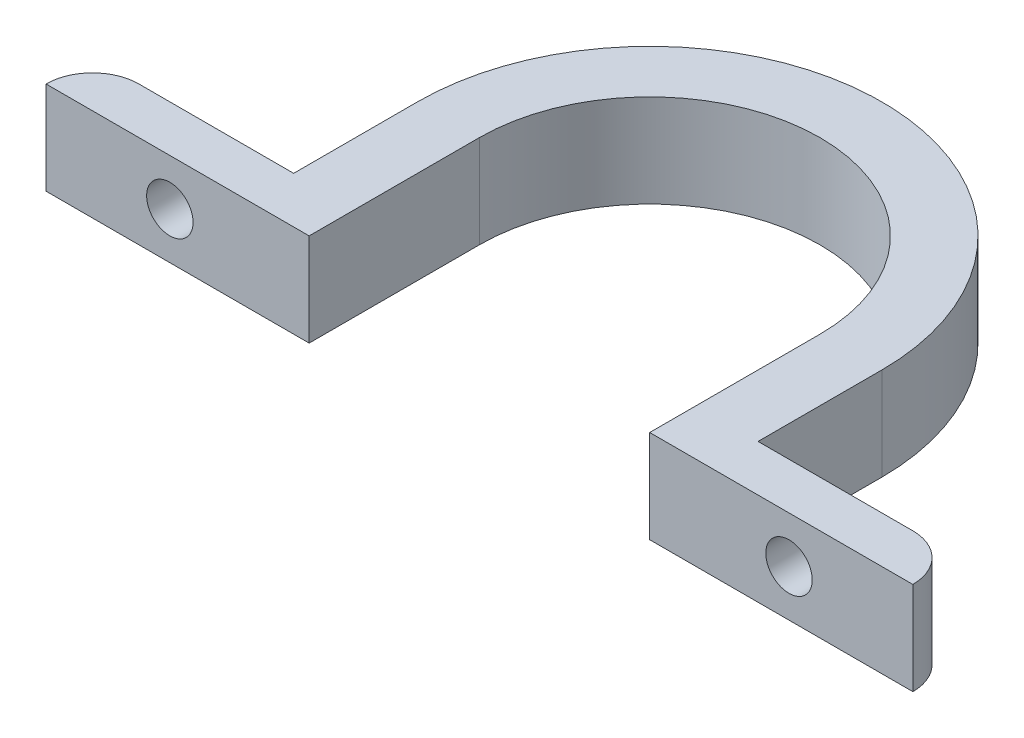
SolidWorks part; units mm, degrees
ref_plane "Plan de face" through (0, 0, 0) normal (0, 0, 1) x (1, 0, 0)
ref_plane "Plan de dessus" through (0, 0, 0) normal (0, 1, 0) x (1, 0, 0)
ref_plane "Plan de droite" through (0, 0, 0) normal (1, 0, 0) x (0, 0, -1)
sketch "Esquisse1" plane through (0, 0, 0) normal (0, 1, 0) x (1, 0, 0)
  line L2 (24, 0.5) -> (24, -10.5)
  line L3 (24, -10.5) -> (41, -10.5)
  line L4 (38, -7.5) -> (28, -7.5)
  line L6 (13, 0) -> (13, 17.6683) construction
  line L7 (13, -10.5) -> (-3.8365, -10.5) construction
  line L8 (38, -6.3228) -> (38, 14.4487) construction
  line L14 (28, -7.5) -> (28, 0.5)
  line L15 (2, -10.5) -> (-15, -10.5)
  line L16 (2, 0.5) -> (2, -10.5)
  line L17 (-2, -7.5) -> (-2, 0.5)
  line L18 (-12, -7.5) -> (-2, -7.5)
  arc A0 (2, 0.5) -> (24, 0.5) centre (13, 0.5) cw
  arc A1 (-2, 0.5) -> (28, 0.5) centre (13, 0.5) cw
  circle A2 centre (13, 0.5) radius 11 construction
  arc A3 (41, -10.5) -> (38, -7.5) centre (38, -10.5) ccw
  arc A4 (-15, -10.5) -> (-12, -7.5) centre (-12, -10.5) cw
  dimension "D1" = 11
  dimension "D2" = 15
  dimension "D3" = 3
  dimension "D6" = 10
  dimension "D4" = 4
  dimension "D5" = 3
extrude "Boss.-Extru.2" add sketch "Esquisse1" along normal blind 6
ref_plane "Plan1" through (-12, 6, 7.5) normal (-1, 0, 0) x (0, 0, 1)
sketch "Esquisse3" plane through (0, 0, 7.5) normal (0, 0, -1) x (-1, 0, 0)
  line L0 (-13, 6) -> (-13, 18.6764) construction
  line L3 (-28, 3) -> (-26.3652, 3) construction
  circle A0 centre (-33, 3) radius 1.5
  circle A1 centre (7, 3) radius 1.5
  dimension "D1" = 3
  dimension "D2" = 40
extrude "Enlèv. mat.-Extru.1" cut sketch "Esquisse3" against normal through all
